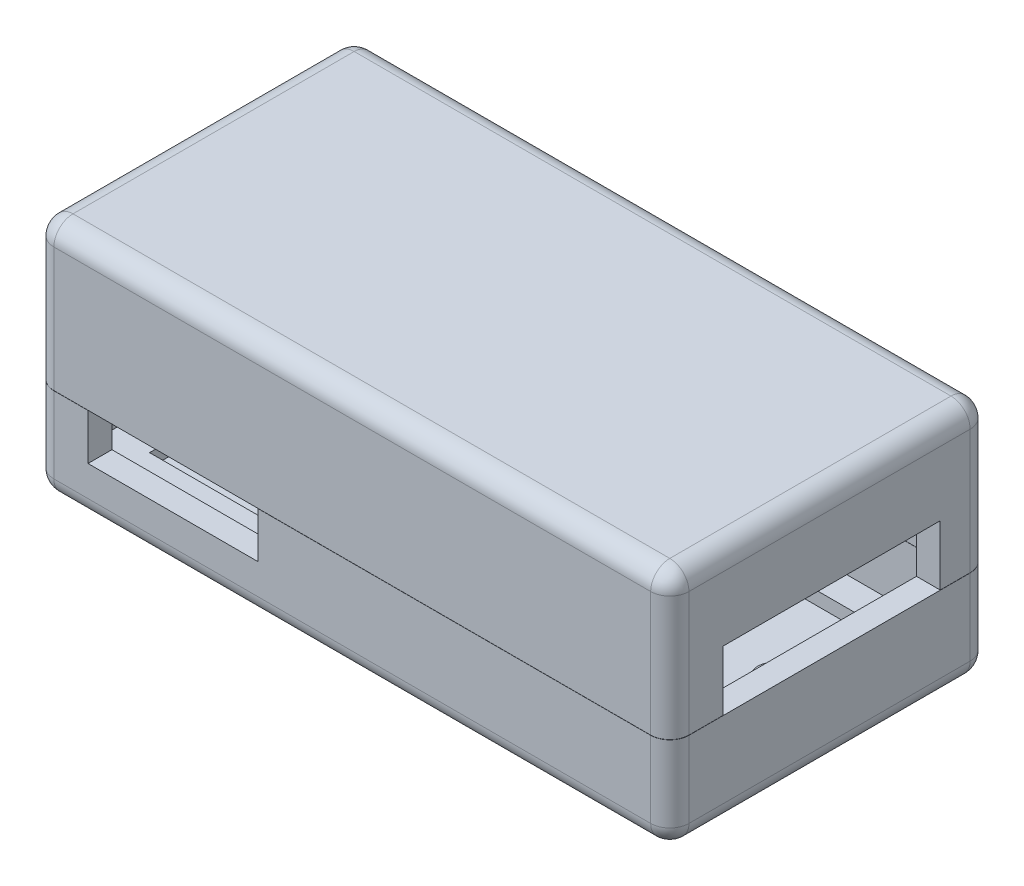
SolidWorks part; units mm, degrees
ref_plane "Front Plane" through (0, 0, 0) normal (0, 0, 1) x (1, 0, 0)
ref_plane "Top Plane" through (0, 0, 0) normal (0, 1, 0) x (1, 0, 0)
ref_plane "Right Plane" through (0, 0, 0) normal (1, 0, 0) x (0, 0, -1)
sketch "Sketch1" plane through (0, 0, 0) normal (0, 1, 0) x (1, 0, 0)
  line L1 (-42.164, -21.209) -> (42.164, -21.209)
  line L2 (-42.164, -21.209) -> (-42.164, 21.209)
  line L3 (-42.164, 21.209) -> (42.164, 21.209)
  line L4 (42.164, -21.209) -> (42.164, 21.209)
  line L5 (-42.164, -21.209) -> (42.164, 21.209) construction
  line L6 (-42.164, 21.209) -> (42.164, -21.209) construction
  point P0 (0, 0)
  dimension "D1" = 84.328
  dimension "D2" = 42.418
extrude "Boss-Extrude1" add sketch "Sketch1" along normal blind 31.75 contours L2 L3 L4 L1
sketch "Sketch2" plane through (0, 0, 21.209) normal (0, 0, 1) x (1, 0, 0)
  line L0 (-42.164, 31.75) -> (-42.164, 0) construction
  line L1 (-35.0901, 6.5761) -> (-12.5222, 6.5761)
  line L2 (-35.0901, 6.5761) -> (-35.0901, 12.6746)
  line L3 (-35.0901, 12.6746) -> (-12.5222, 12.6746)
  line L4 (-12.5222, 6.5761) -> (-12.5222, 12.6746)
  line L5 (-42.164, 0) -> (42.164, 0) construction
  dimension "D1" = 7.0739
  dimension "D2" = 29.6418
  dimension "D3" = 6.5761
  dimension "D4" = 12.6746
extrude "Cut-Extrude1" cut sketch "Sketch2" against normal through all
shell "Shell1" thickness 3.175
sketch "Sketch4" plane through (-42.164, 0, 0) normal (-1, 0, 0) x (0, 0, 1)
  line L1 (-3.937, 6.5761) -> (3.937, 6.5761)
  line L2 (-3.937, 6.5761) -> (-3.937, 12.6746)
  line L3 (-3.937, 12.6746) -> (3.937, 12.6746)
  line L4 (3.937, 6.5761) -> (3.937, 12.6746)
  line L8 (-21.209, 31.75) -> (-21.209, 0) construction
  point P4 (0, 6.5761)
  dimension "D1" = 17.272
extrude "Cut-Extrude3" cut sketch "Sketch4" against normal up to next contours L2 L3 L4 L1
fillet "Fillet1" radius 2.54 12 edges at (-42.164, 15.875, 21.209) (42.164, 15.875, 21.209) (42.164, 15.875, -21.209) (-42.164, 15.875, -21.209) (42.164, 0, 0) (0, 0, -21.209) (-42.164, 0, 0) (0, 0, 21.209) (-42.164, 31.75, 0) (0, 31.75, -21.209) (42.164, 31.75, 0) (0, 31.75, 21.209)
sketch "Sketch5" plane through (0, 0, 21.209) normal (0, 0, 1) x (1, 0, 0)
  line L0 (-12.5222, 12.6746) -> (-35.0901, 12.6746) construction
  line L1 (-44.3024, 12.6746) -> (44.7358, 12.6746)
  line L2 (-44.3024, 12.6746) -> (-44.3024, 12.7)
  line L3 (-44.3024, 12.7) -> (44.7358, 12.7)
  line L4 (44.7358, 12.6746) -> (44.7358, 12.7)
  dimension "D1" = 0.0254
extrude "Cut-Extrude4" cut sketch "Sketch5" against normal through all
sketch "Sketch6" plane through (0, 3.175, 0) normal (0, 1, 0) x (1, 0, 0)
  line L0 (-38.989, 18.034) -> (38.989, 18.034)
  line L1 (38.989, 18.034) -> (38.989, -18.034)
  line L2 (38.989, -18.034) -> (-38.989, -18.034)
  line L3 (-38.989, -18.034) -> (-38.989, 18.034)
  line L4 (-33.909, -14.224) -> (-33.909, 14.224)
  line L5 (-33.909, 14.224) -> (35.179, 14.224)
  line L6 (35.179, 14.224) -> (35.179, 6.35)
  line L7 (35.179, -14.224) -> (-33.909, -14.224)
  line L8 (35.179, -6.35) -> (35.179, -14.224)
  line L9 (35.179, 6.35) -> (31.623, 6.35)
  line L11 (35.179, -6.35) -> (31.623, -6.35)
  line L12 (31.623, 6.35) -> (31.623, -6.35)
  point P16 (31.623, 0)
  point P19 (38.989, 0)
  dimension "D1" = 3.81
  dimension "D2" = 5.08
  dimension "D3" = 3.81
  dimension "D4" = 3.81
  dimension "D5" = 7.366
  dimension "D6" = 12.7
extrude "Boss-Extrude2" add sketch "Sketch6" along normal blind 1.7501
sketch "Sketch7" plane through (0, 4.9251, 0) normal (0, 1, 0) x (1, 0, 0)
  line L0 (31.623, -6.35) -> (31.623, 6.35) construction
  line L2 (38.989, -18.034) -> (38.989, 18.034) construction
  circle A0 centre (34.925, 0) radius 2.286
  point P2 (0, 0)
  point P6 (31.623, 0)
  dimension "D1" = 4.572
  dimension "D2" = 4.064
extrude "Boss-Extrude3" add sketch "Sketch7" along normal blind 1.6002
sketch "Sketch9" plane through (42.164, 0, 0) normal (1, 0, 0) x (0, 0, -1)
  line L0 (-18.669, 12.7) -> (18.669, 12.7) construction
  line L1 (-14.175, 12.7) -> (14.6952, 12.7)
  line L2 (-14.175, 12.7) -> (-14.175, 20.6689)
  line L3 (-14.175, 20.6689) -> (14.6952, 20.6689)
  line L4 (14.6952, 12.7) -> (14.6952, 20.6689)
extrude "Cut-Extrude5" cut sketch "Sketch9" against normal up to next (3.175 mm away)
equation "\"wallThickness\"= 1 / 8in"
equation "\"D1@Sketch1\"=3.07in+2*\"wallThickness\""
equation "\"D2@Sketch1\"=1.42in+2*\"wallThickness\""
equation "\"D1@Sketch2\"=.1535+\"wallThickness\""
equation "\"D2@Sketch2\"=1.042+\"wallThickness\""
equation "\"D3@Sketch2\"=.1339+\"wallThickness\""
equation "\"D4@Sketch2\"=.374+\"wallThickness\""
equation "\"D1@Sketch4\"=0.555in+\"wallThickness\""
equation "\"D1@Shell1\"= \"wallThickness\""
equation "\"D2@Sketch7\"=0.15in+.01"
equation "\"D1@Sketch7\"=0.20in-.02"
